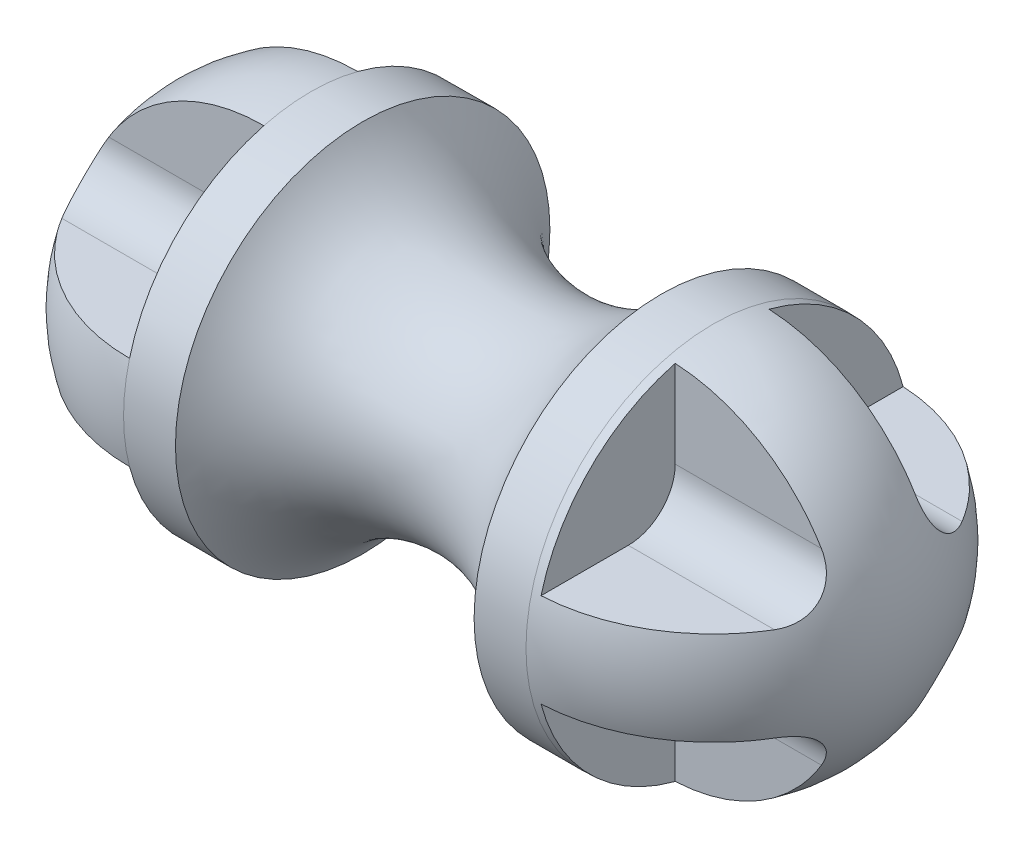
SolidWorks part; units mm, degrees
ref_plane "Front Plane" through (0, 0, 0) normal (0, 0, 1) x (1, 0, 0)
ref_plane "Top Plane" through (0, 0, 0) normal (0, 1, 0) x (1, 0, 0)
ref_plane "Right Plane" through (0, 0, 0) normal (1, 0, 0) x (0, 0, -1)
sketch "Sketch1" plane through (0, 0, 0) normal (0, 1, 0) x (1, 0, 0)
  line L0 (-43.8421, 0) -> (41.9477, 0) construction
  line L1 (-43.8421, 39.918) -> (-32.782, 39.918)
  line L3 (30.8876, 39.918) -> (41.9477, 39.918)
  line L4 (-83.7601, 0) -> (81.8657, 0)
  arc A0 (-43.8421, 39.918) -> (-83.7601, 0) centre (-43.8421, 0) ccw
  arc A1 (81.8657, 0) -> (41.9477, 39.918) centre (41.9477, 0) ccw
  arc A2 (-32.782, 39.918) -> (30.8876, 39.918) centre (-0.9472, 60.2153) ccw
  point P3 (-0.9472, 0)
revolve "Revolve1" add sketch "Sketch1" angle 360 about L0
sketch3d "3DSketch1"
  circle A0 centre (-43.8421, 0, 0) radius 39.918 construction
  point P2 (-83.7601, 0, 0)
sketch "Sketch2" plane through (-43.8421, 0, 0) normal (1, 0, 0) x (0, 0, -1)
  line L0 (-10, 38.6451) -> (-10, 20)
  line L1 (10, 38.6451) -> (10, 20)
  line L2 (-38.6451, 10) -> (-20, 10)
  line L3 (-38.6451, -10) -> (-20, -10)
  line L4 (20, 10) -> (38.6451, 10)
  line L5 (-10, -20) -> (-10, -38.6451)
  line L6 (10, -20) -> (10, -38.6451)
  line L7 (20, -10) -> (38.6451, -10)
  arc A0 (38.6451, 10) -> (10, 38.6451) centre (0, 0) ccw
  circle A1 centre (0, 0) radius 39.918
  arc A2 (-10, 38.6451) -> (-38.6451, 10) centre (0, 0) ccw
  arc A3 (-38.6451, -10) -> (-10, -38.6451) centre (0, 0) ccw
  arc A4 (10, -38.6451) -> (38.6451, -10) centre (0, 0) ccw
  arc A5 (-10, -20) -> (-20, -10) centre (-20, -20) ccw
  arc A6 (10, -20) -> (20, -10) centre (20, -20) cw
  arc A7 (20, 10) -> (10, 20) centre (20, 20) cw
  arc A8 (-20, 10) -> (-10, 20) centre (-20, 20) ccw
  point P18 (10, -10)
  dimension "D6" = 10
  dimension "D2" = 20
  dimension "D3" = 10
  dimension "D4" = 10
  dimension "D5" = 10
  dimension "D1" = 0
extrude "Cut-Extrude1" cut sketch "Sketch2" against normal blind 110
mirror "Mirror1" about plane through (0, 0, 0) normal (1, 0, 0) of "Cut-Extrude1"
